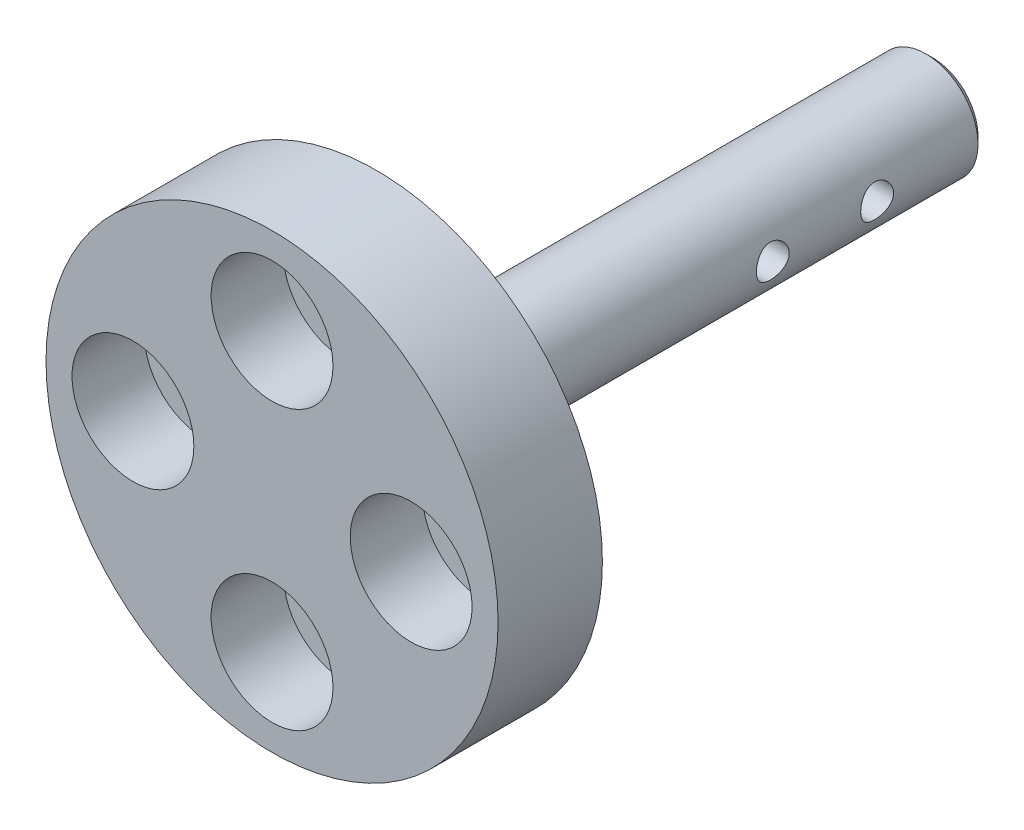
SolidWorks part; units mm, degrees
ref_plane "Front Plane" through (0, 0, 0) normal (0, 0, 1) x (1, 0, 0)
ref_plane "Top Plane" through (0, 0, 0) normal (0, 1, 0) x (1, 0, 0)
ref_plane "Right Plane" through (0, 0, 0) normal (1, 0, 0) x (0, 0, -1)
sketch "Sketch1" plane through (0, 0, 0) normal (0, 0, 1) x (1, 0, 0)
  circle A0 centre (0, 0) radius 20.6375
  dimension "D1" = 41.275
extrude "Boss-Extrude1" add sketch "Sketch1" along normal blind 9.525
sketch "Sketch3" plane through (0, 0, 9.525) normal (0, 0, 1) x (1, 0, 0)
  circle A0 centre (0, 12.7) radius 5.5626
  dimension "D1" = 11.1252
  dimension "D2" = 12.7
extrude "Cut-Extrude1" cut sketch "Sketch3" against normal blind 6.604
pattern_circular "CirPattern1" count 4 over 360 about axis through (0, 0, 0) along (0, 0, 1) of "Cut-Extrude1"
sketch "Sketch10" plane through (0, 0, 0) normal (0, 0, -1) x (-1, 0, 0)
  circle A0 centre (0, 0) radius 4.7625
  dimension "D1" = 9.525
extrude "Boss-Extrude3" add sketch "Sketch10" along normal blind 50.8
sketch "Sketch11" plane through (0, 0, 0) normal (1, 0, 0) x (0, 0, -1)
  line L0 (50.8, -4.7625) -> (50.8, 4.7625) construction
  circle A0 centre (31.4325, 0) radius 1.5
  circle A1 centre (40.9575, 0) radius 1.5
  dimension "D1" = 3
  dimension "D2" = 3
  dimension "D3" = 9.525
  dimension "D4" = 9.8425
extrude "Cut-Extrude3" cut sketch "Sketch11" against normal through all and the other way through all
sketch "Sketch12" plane through (0, 0, 0) normal (0, 1, 0) x (1, 0, 0)
  line L0 (-20.6375, 0) -> (-4.7625, 7.9375)
  line L1 (20.6375, 0) -> (-20.6375, 0) construction
  line L2 (-4.7625, 29.9325) -> (-4.7625, 0) construction
  line L3 (0, 0) -> (0, 16.1153) construction
  line L4 (-4.7625, 7.9375) -> (-4.7625, 0)
  line L5 (-4.7625, 0) -> (-20.6375, 0)
  dimension "D1" = 7.9375
  dimension "D2" = 20.6375
revolve "Revolve1" add sketch "Sketch12" angle 360 about L3
sketch "Sketch13" plane through (0, 0, 2.921) normal (0, 0, 1) x (1, 0, 0)
  circle A0 centre (-12.7, 0) radius 3.175
  dimension "D1" = 6.35
extrude "Cut-Extrude4" cut sketch "Sketch13" against normal through all
pattern_circular "CirPattern2" count 4 over 360 about axis through (0, 0, 0) along (0, 0, 1) of "Cut-Extrude4"
chamfer "Chamfer1" distance 0.635 angle 45 1 edges at (-4.7625, 0, -50.8)
